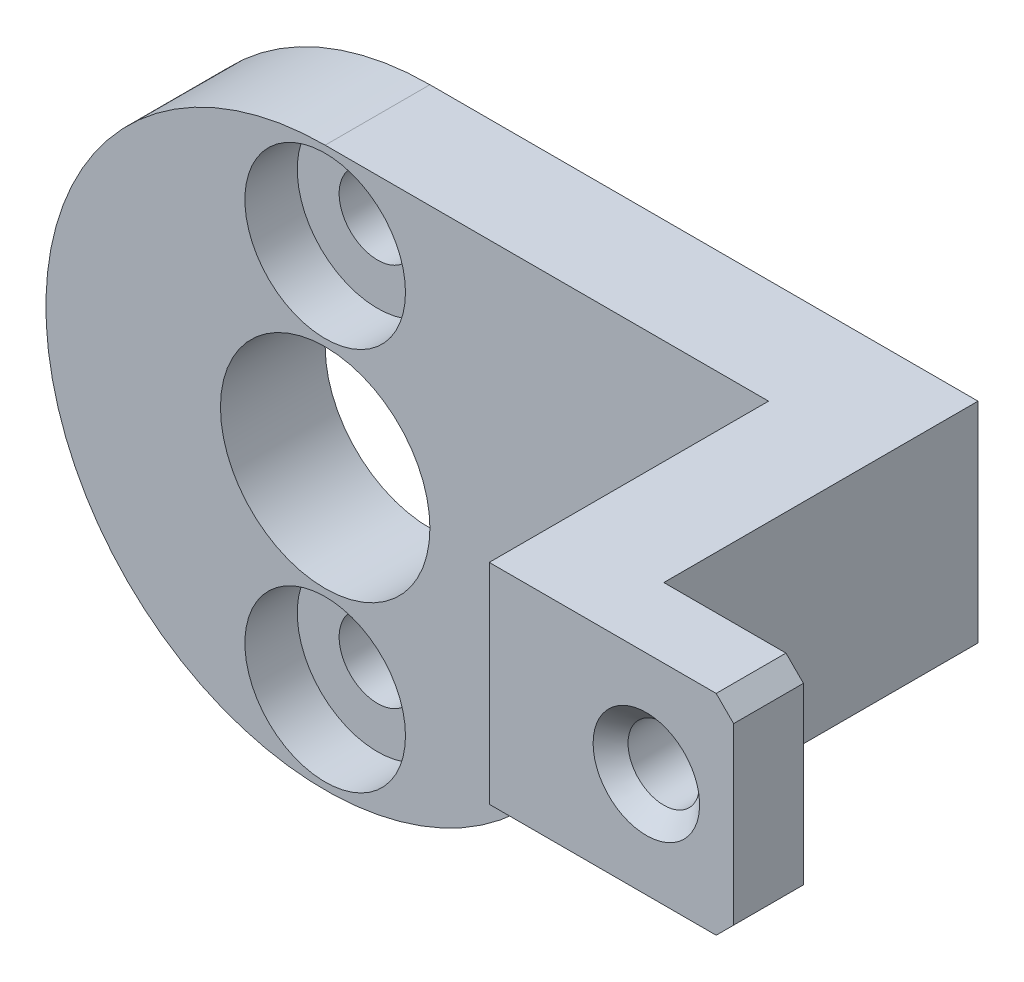
SolidWorks part; units mm, degrees
material "2A12"
ref_plane "前视基准面" through (0, 0, 0) normal (0, 0, 1) x (1, 0, 0)
ref_plane "上视基准面" through (0, 0, 0) normal (0, 1, 0) x (1, 0, 0)
ref_plane "右视基准面" through (0, 0, 0) normal (1, 0, 0) x (0, 0, -1)
sketch "草图1" plane through (0, 0, 0) normal (0, 0, 1) x (1, 0, 0)
  line L0 (0, 8) -> (0, -8) construction
  line L1 (-7.15, 8) -> (7.15, 8)
  line L2 (-7.15, 8) -> (-7.15, -8)
  line L3 (-7.15, -8) -> (7.15, -8)
  line L4 (7.15, 8) -> (7.15, -8)
  dimension "D1" = 14.3
  dimension "D2" = 16
extrude "拉伸1" add sketch "草图1" along normal mid plane 2
sketch "草图2" plane through (0, 0, -1) normal (0, 0, 1) x (1, 0, 0)
  line L1 (7.15, -16.5) -> (5.15, -16.5)
  line L2 (7.15, -16.5) -> (7.15, 16.5)
  line L3 (7.15, 16.5) -> (5.15, 16.5)
  line L4 (5.15, -16.5) -> (5.15, 16.5)
  line L5 (0, 0) -> (5.15, 0) construction
  line L6 (7.15, -8) -> (7.15, 8) construction
  dimension "D1" = 2
  dimension "D2" = 33
extrude "拉伸2" [suppressed] add sketch "草图2" along normal blind 4.5
sketch "草图3" plane through (0, 0, -1) normal (0, 0, -1) x (-1, 0, 0)
  line L0 (2.55, 0) -> (7.15, 0) construction
  line L1 (7.15, 8) -> (7.15, -8) construction
  circle A0 centre (2.55, 0) radius 3
  dimension "D1" = 6
  dimension "D2" = 4.6
extrude "拉伸3" cut sketch "草图3" against normal blind 10
sketch "草图4" plane through (0, 0, -1) normal (0, 0, -1) x (-1, 0, 0)
  line L0 (2.55, 5) -> (2.55, -5) construction
  circle A0 centre (2.55, 5) radius 1.25
  circle A1 centre (2.55, -5) radius 1.25
  circle A2 centre (2.55, 0) radius 3 construction
  circle A3 centre (2.55, 0) radius 3 construction
  dimension "D2" = 2.5
  dimension "D1" = 10
extrude "拉伸4" cut sketch "草图4" against normal up to surface (2 mm away) up to face at (0.45, 0, 1)
sketch "草图6" [suppressed] plane through (3.61, 0, 0) normal (-1, 0, 0) x (0, 0, 1)
  line L0 (1.25, -14) -> (1.25, 14) construction
  line L1 (0, 0) -> (1.25, 0) construction
  line L2 (1.25, -16.5) -> (1.25, -14) construction
  line L3 (3.5, -16.5) -> (-1, -16.5) construction
  dimension "D1" = 28
hole_wizard "M2.5 螺纹孔1" [suppressed] positions "3D草图1" profile "草图7" tap size "M2.5" standard "GB"
sketch3d "3D草图1" [suppressed]
  point P0 (3.61, -14, 1.25)
  point P3 (3.61, 14, 1.25)
sketch "草图7" plane through (3.61, -14, 1.25) normal (0, 1, 0) x (0, 0, 1)
  line L0 (0, 0) -> (0, 6.9659)
  line L1 (0, 6.9659) -> (1.025, 6.35)
  line L2 (1.025, 6.35) -> (1.025, 0)
  line L5 (1.025, 0) -> (0, 0)
  line L10 (0, 6.9659) -> (-1.025, 6.35) construction
  line L11 (0, -6.35) -> (0, 107.95) construction
  dimension "螺纹孔钻头直径" = 2.05
  dimension "螺纹孔钻头深度" = 6.35
  dimension "导头角度" = 118
cosmetic thread "孔螺蚊线1" parameters "D1"=2, "D2"=2.5
cosmetic thread "孔螺蚊线2" parameters "D1"=2, "D2"=2.5
chamfer "倒角1" [suppressed] distance 1 angle 45
chamfer "倒角2" distance 3 angle 45 2 edges at (-7.15, 8, 0) (-7.15, -8, 0)
chamfer "倒角3" [suppressed] distance 0.3 angle 45
sketch "Sketch1" plane through (0, 0, 1) normal (0, 0, 1) x (1, 0, 0)
  line L0 (-4.15, -8) -> (7.15, -8) construction
  line L1 (7.15, 8) -> (5.15, 8)
  line L2 (7.15, 8) -> (7.15, -8)
  line L3 (7.15, -8) -> (5.15, -8)
  line L4 (5.15, 8) -> (5.15, -8)
  dimension "D1" = 2
extrude "Extrude1" add sketch "Sketch1" along normal blind 8
sketch "Sketch2" plane through (7.15, 0, 0) normal (1, 0, 0) x (0, 0, -1)
  line L0 (-9, -8) -> (1, -8) construction
  line L1 (-9, 8) -> (-7, 8)
  line L2 (-9, 8) -> (-9, -8)
  line L3 (-9, -8) -> (-7, -8)
  line L4 (-7, 8) -> (-7, -8)
  dimension "D1" = 2
extrude "Extrude2" add sketch "Sketch2" along normal blind 10
sketch "Sketch3" plane through (0, -8, 0) normal (0, -1, 0) x (1, 0, 0)
  line L0 (-4.15, -1) -> (7.15, -1) construction
  line L1 (2.85, -1) -> (17.15, -1)
  line L2 (2.85, -1) -> (2.85, 9)
  line L3 (2.85, 9) -> (17.15, 9)
  line L4 (17.15, -1) -> (17.15, 9)
  line L5 (-7.15, -1) -> (-7.15, 1) construction
  dimension "D1" = 10
extrude "Extrude3" cut sketch "Sketch3" against normal blind 10
sketch "Sketch4" plane through (0, 0, 9) normal (0, 0, 1) x (1, 0, 0)
  line L0 (17.15, 5) -> (14.65, 5)
  line L1 (17.15, 8) -> (17.15, 2) construction
  line L2 (14.65, 5) -> (8.65, 5)
  line L3 (8.65, 5) -> (5.15, 5)
  line L4 (5.15, 8) -> (5.15, 2) construction
  dimension "D1" = 6
  dimension "D2" = 2.5
hole_wizard "M2.5 螺纹孔2" positions "3DSketch1" profile "Sketch5" tap size "M2.5" standard "GB"
sketch3d "3DSketch1"
  point P3 (14.65, 5, 9)
sketch "Sketch5" plane through (14.65, 5, 9) normal (1, 0, 0) x (0, -1, 0)
  line L0 (0, 0) -> (0, 7.8659)
  line L1 (0, 7.8659) -> (1.025, 7.25)
  line L2 (1.025, 7.25) -> (1.025, 0)
  line L5 (1.025, 0) -> (0, 0)
  line L10 (0, 7.8659) -> (-1.025, 7.25) construction
  line L11 (0, -6.35) -> (0, 107.95) construction
  dimension "Tap Drill Dia." = 2.05
  dimension "Tap Drill Depth" = 7.25
  dimension "Drill Angle" = 118
cosmetic thread "Hole Thread1" parameters "D1"=2, "D2"=2.5
chamfer "Chamfer1" distance 3 angle 45 1 edges at (2.85, -8, 0)
chamfer "Chamfer2" [suppressed] distance 0.5 angle 45
chamfer "Chamfer3" [suppressed] distance 0.5 angle 45
chamfer "Chamfer4" distance 0.5 angle 45 1 edges at (15.675, 5, 9)
sketch "Sketch6" plane through (0, 8, 0) normal (0, 1, 0) x (-1, 0, 0)
  line L0 (-17.15, 7) -> (-7.15, 7) construction
  line L1 (-10.65, 7) -> (-12.65, 7)
  line L2 (-10.65, 7) -> (-10.65, 1)
  line L3 (-7.15, -1) -> (-12.65, -1)
  line L4 (-12.65, 7) -> (-12.65, -1)
  line L6 (-5.15, 1) -> (-10.65, 1)
  line L7 (-5.15, 1) -> (-7.15, -1)
  line L8 (-17.15, 7) -> (-17.15, 9) construction
  dimension "D1" = 2
  dimension "D2" = 4.5
extrude "Extrude4" add sketch "Sketch6" against normal up to surface (6 mm away) up to face at (8.075, 2, 4)
sketch "Sketch7" plane through (0, 2, 0) normal (0, -1, 0) x (1, 0, 0)
  line L0 (5.15, 1) -> (5.15, 9) construction
  line L1 (7.15, 1) -> (5.15, 1)
  line L2 (7.15, 1) -> (7.15, 7)
  line L3 (7.15, 7) -> (5.15, 7)
  line L4 (5.15, 1) -> (5.15, 7)
  line L5 (10.65, 7) -> (7.15, 7) construction
extrude "Extrude5" cut sketch "Sketch7" against normal blind 10
chamfer "Chamfer5" distance 0.5 angle 45 4 edges at (17.15, 8, 8) (17.15, 2, 8) (5.15, 2, 8)
sketch "Sketch8" plane through (0, 0, 1) normal (0, 0, 1) x (1, 0, 0)
  line L0 (10.65, 8) -> (-4.15, 8) construction
  line L1 (-10.55, -8) -> (5.45, -8)
  line L2 (-10.55, -8) -> (-10.55, 8)
  line L3 (-10.55, 8) -> (5.45, 8)
  line L4 (5.45, -8) -> (5.45, 8)
  line L5 (-10.55, -8) -> (5.45, 8) construction
  line L6 (-10.55, 8) -> (5.45, -8) construction
  circle A0 centre (-2.55, 0) radius 3 construction
  circle A1 centre (-2.55, 0) radius 3
  point P0 (-2.55, 0)
  dimension "D1" = 16
extrude "Extrude6" add sketch "Sketch8" against normal up to surface (2 mm away)
sketch "Sketch9" plane through (0, 0, 1) normal (0, 0, 1) x (1, 0, 0)
  line L0 (-2.55, 0) -> (-2.55, 5.5) construction
  line L1 (-2.55, 0) -> (-2.55, -5.5) construction
  circle A0 centre (-2.55, -5.5) radius 1.1
  circle A1 centre (-2.55, 5.5) radius 1.1
  circle A2 centre (-2.55, 0) radius 3 construction
  circle A3 centre (-2.55, 0) radius 3 construction
  dimension "D1" = 5.5
  dimension "D2" = 2.2
extrude "Extrude7" cut sketch "Sketch9" against normal through all
sketch "Sketch11" plane through (0, 0, 1) normal (0, 0, 1) x (1, 0, 0)
  line L0 (-10.55, -8) -> (5.45, -8) construction
  line L1 (-10.55, 8) -> (-8.55, 8)
  line L2 (-10.55, 8) -> (-10.55, -8)
  line L3 (-10.55, -8) -> (-8.55, -8)
  line L4 (-8.55, 8) -> (-8.55, -8)
  dimension "D1" = 2
extrude "Extrude9" [suppressed] cut sketch "Sketch11" against normal blind 10
fillet "Fillet1" [suppressed] radius 1
sketch "Sketch10" [suppressed] plane through (0, 0, 1) normal (0, 0, 1) x (1, 0, 0)
  line L0 (-1.9, 0) -> (-6.9, 0) construction
  line L2 (-6.9, -7) -> (-6.9, -1.25) construction
  line L3 (-6.9, 2) -> (-1.9, 2)
  line L4 (-6.9, 2) -> (-6.9, -2)
  line L5 (-6.9, -2) -> (-1.9, -2)
  line L6 (-1.9, 2) -> (-1.9, -2)
  dimension "D2" = 4
extrude "Extrude8" [suppressed] cut sketch "Sketch10" against normal blind 10
chamfer "Chamfer7" [suppressed] distance 3 angle 45
sketch "Sketch12" plane through (10.65, 0, 0) normal (-1, 0, 0) x (0, 0, 1)
  line L4 (1, 2) -> (7, 2)
  line L5 (7, 2) -> (7, 8)
  line L6 (7, 8) -> (1, 8)
  line L7 (1, 8) -> (1, 2)
  line L8 (1, 2) -> (7, 2)
  line L9 (7, 2) -> (7, 8)
  line L10 (7, 8) -> (1, 8)
  line L11 (1, 8) -> (1, 2)
  dimension "D1" = 0
extrude "Extrude10" add sketch "Sketch12" along normal blind 0.5
sketch "Sketch13" plane through (12.65, 0, 0) normal (1, 0, 0) x (0, 0, -1)
  line L4 (-7, 2) -> (1, 2)
  line L5 (1, 2) -> (1, 8)
  line L6 (1, 8) -> (-7, 8)
  line L7 (-7, 8) -> (-7, 2)
  line L8 (-7, 2) -> (1, 2)
  line L9 (1, 2) -> (1, 8)
  line L10 (1, 8) -> (-7, 8)
  line L11 (-7, 8) -> (-7, 2)
  dimension "D1" = 0
extrude "Extrude11" add sketch "Sketch13" along normal blind 0.5
fillet "Fillet2" [suppressed] radius 1
sketch "Sketch14" plane through (0, 0, 1) normal (0, 0, 1) x (1, 0, 0)
  line L9 (10.15, 2) -> (10.15, 8)
  line L10 (10.15, 8) -> (-10.55, 8)
  line L12 (-10.55, 8) -> (-10.55, -8)
  line L14 (-10.55, -8) -> (5.45, -8)
  line L16 (5.45, -8) -> (5.45, 2)
  line L17 (5.45, 2) -> (10.15, 2)
  line L18 (10.15, 2) -> (10.15, 8)
  line L19 (10.15, 8) -> (-10.55, 8)
  line L21 (-10.55, 8) -> (-10.55, -8)
  line L23 (-10.55, -8) -> (5.45, -8)
  line L25 (5.45, -8) -> (5.45, 2)
  line L26 (5.45, 2) -> (10.15, 2)
  circle A0 centre (-2.55, 0) radius 3 construction
  circle A1 centre (-2.55, 0) radius 3
  circle A3 centre (-2.55, 5.5) radius 1.1 construction
  circle A5 centre (-2.55, 5.5) radius 1.1
  circle A6 centre (-2.55, -5.5) radius 1.1 construction
  circle A7 centre (-2.55, -5.5) radius 1.1
  dimension "D1" = 0
extrude "Extrude12" [suppressed] add sketch "Sketch14" along normal blind 2
chamfer "Chamfer9" [suppressed] distance 0.5 angle 45
fillet "Fillet3" [suppressed] radius 2
sketch "Sketch15" plane through (0, 0, -1) normal (0, 0, -1) x (-1, 0, 0)
  line L9 (10.55, -8) -> (10.55, 8)
  line L11 (10.55, 8) -> (-13.15, 8)
  line L12 (-13.15, 8) -> (-13.15, 2)
  line L13 (-13.15, 2) -> (-5.45, 2)
  line L14 (-5.45, 2) -> (-5.45, -8)
  line L16 (-5.45, -8) -> (10.55, -8)
  line L18 (10.55, -8) -> (10.55, 8)
  line L20 (10.55, 8) -> (-13.15, 8)
  line L21 (-13.15, 8) -> (-13.15, 2)
  line L22 (-13.15, 2) -> (-5.45, 2)
  line L23 (-5.45, 2) -> (-5.45, -8)
  line L25 (-5.45, -8) -> (10.55, -8)
  circle A0 centre (2.55, 5.5) radius 1.1 construction
  circle A1 centre (2.55, 5.5) radius 1.1
  circle A2 centre (2.55, -5.5) radius 1.1 construction
  circle A3 centre (2.55, -5.5) radius 1.1
  circle A4 centre (2.55, 0) radius 3 construction
  circle A5 centre (2.55, 0) radius 3
  dimension "D1" = 0
extrude "Extrude13" add sketch "Sketch15" along normal blind 1
chamfer "Chamfer10" [suppressed] distance 0.5 angle 45
fillet "Fillet4" [suppressed] radius 3
sketch "草图9" plane through (0, 0, -2) normal (0, 0, -1) x (-1, 0, 0)
  line L0 (-5.45, 0) -> (-5.45, -9.751)
  line L1 (-5.45, -9.751) -> (10.8727, -9.751)
  line L2 (10.8727, -9.751) -> (10.8727, 8)
  line L3 (10.8727, 8) -> (10.55, 8)
  line L4 (-5.45, 2) -> (-5.45, -8) construction
  line L5 (10.55, 8) -> (2.55, 8)
  arc A0 (-5.45, 0) -> (2.55, 8) centre (2.55, 0) ccw
  dimension "D1" = 16
extrude "切除-拉伸1" cut sketch "草图9" against normal blind 10 contours L2 L3 L5 A0 L0 L1
hole_wizard "打孔尺寸(%根据)内六角圆柱头螺钉的类型1" positions "草图11" profile "草图10" counterbore size "M2" standard "GB" end condition through all
sketch "草图11" plane through (0, 0, 1) normal (0, 0, 1) x (1, 0, 0)
  point P0 (-2.55, 5.5)
  point P2 (-2.55, -5.5)
sketch "草图10" plane through (-2.55, 5.5, 1) normal (1, 0, 0) x (0, -1, 0)
  line L0 (0, 0) -> (0, 3)
  line L1 (0, 3) -> (1.1, 3)
  line L3 (1.1, 3) -> (1.1, 1.5)
  line L4 (1.1, 1.5) -> (2.3, 1.5)
  line L5 (2.3, 1.5) -> (2.3, 0)
  line L7 (2.3, 0) -> (0, 0)
  line L11 (0, -6.35) -> (0, 107.95) construction
  dimension "通孔孔直径" = 2.2
  dimension "通孔孔深度" = 3
  dimension "柱形沉头孔直径" = 4.6
  dimension "柱形沉头孔深度" = 1.5
fillet "圆角3" radius 1 1 edges at (5.45, 2, -0.5)
sketch "草图12" plane through (0, 8, 0) normal (0, 1, 0) x (1, 0, 0)
  line L0 (10.15, -7) -> (10.15, -1) construction
  line L1 (10.15, -4) -> (2.0291, -4)
  line L2 (10.15, -4) -> (10.15, -10.4899)
  line L3 (10.15, -10.4899) -> (2.0291, -10.4899)
  line L4 (2.0291, -4) -> (2.0291, -10.4899)
extrude "切除-拉伸2" cut sketch "草图12" against normal blind 10
